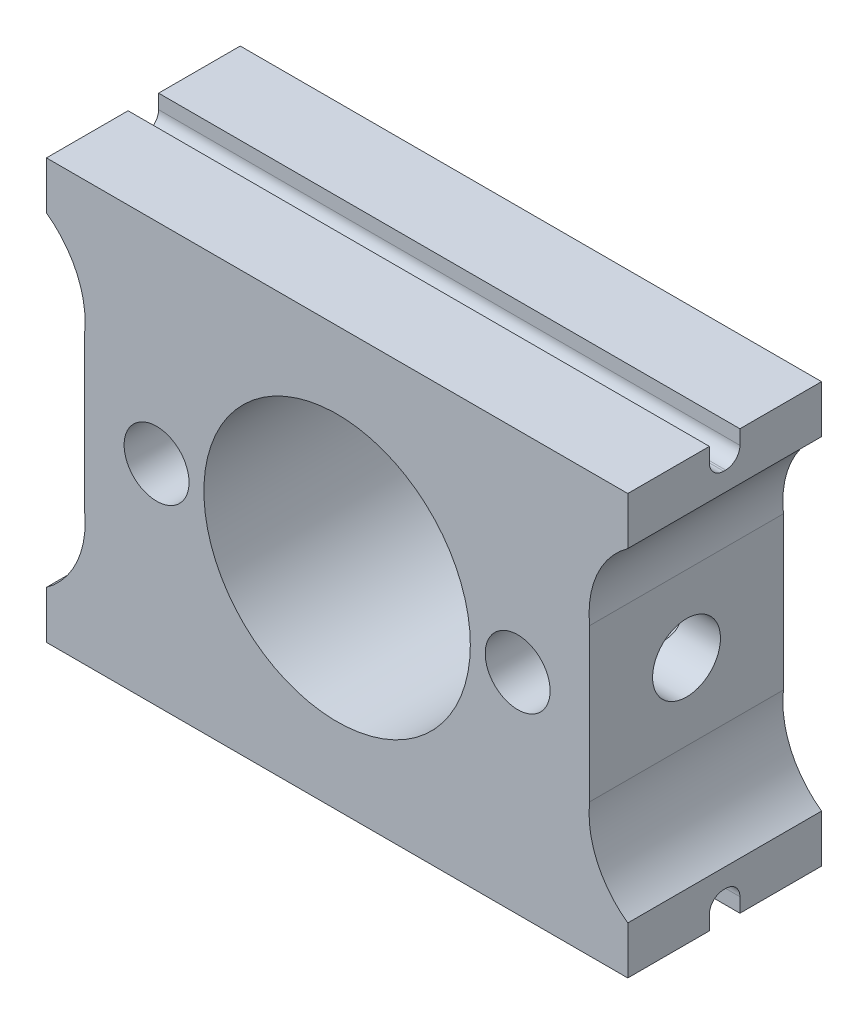
SolidWorks part; units mm, degrees
ref_plane "Front Plane" through (0, 0, 0) normal (0, 0, 1) x (1, 0, 0)
ref_plane "Top Plane" through (0, 0, 0) normal (0, 1, 0) x (1, 0, 0)
ref_plane "Right Plane" through (0, 0, 0) normal (1, 0, 0) x (0, 0, -1)
sketch "Sketch1" plane through (0, 0, 0) normal (0, 0, 1) x (1, 0, 0)
  line L0 (1, 7.5) -> (1, 3.5)
  line L1 (0, 0) -> (15.24, 0)
  line L2 (0, 0) -> (0, 11)
  line L3 (0, 11) -> (15.24, 11)
  line L4 (15.24, 0) -> (15.24, 11)
  line L5 (1, 7.5) -> (1, 11) construction
  line L6 (1, 3.5) -> (1, 0) construction
  line L7 (0, 5.5) -> (15.24, 5.5) construction
  line L8 (7.62, 11) -> (7.62, 0) construction
  line L9 (14.24, 7.5) -> (14.24, 3.5)
  arc A0 (0, 9.75) -> (1, 7.5) centre (-1.4231, 7.7703) cw
  arc A1 (0, 1.25) -> (1, 3.5) centre (-1.4231, 3.2297) ccw
  arc A2 (15.24, 1.25) -> (14.24, 3.5) centre (16.6631, 3.2297) cw
  arc A3 (15.24, 9.75) -> (14.24, 7.5) centre (16.6631, 7.7703) ccw
  circle A4 centre (7.62, 5.5) radius 3.4925
  circle A5 centre (2.8868, 5.5) radius 0.8509
  circle A6 centre (12.3532, 5.5) radius 0.8509
  dimension "D6" = 6.985
  dimension "D1" = 15.24
  dimension "D2" = 11
  dimension "D3" = 4
  dimension "D4" = 1.25
  dimension "D5" = 1
  dimension "D8" = 9.4664
extrude "Boss-Extrude1" add sketch "Sketch1" along normal blind 5.08 contours A3 L4 L3 L2 A0 L0 A1 L1 A2 L9 A4 A5 A6
sketch "Sketch2" plane through (14.24, 0, 0) normal (1, 0, 0) x (0, 0, -1)
  circle A0 centre (-2.54, 5.5) radius 0.89
  dimension "D1" = 1.78
extrude "Cut-Extrude1" cut sketch "Sketch2" against normal blind 2.286
sketch "Sketch3" plane through (1, 0, 0) normal (-1, 0, 0) x (0, 0, 1)
  circle A0 centre (2.54, 5.5) radius 0.89
  dimension "D1" = 1.78
extrude "Cut-Extrude2" cut sketch "Sketch3" against normal blind 2.286
ref_plane "Plane1" through (0, 5.5, 0) normal (0, -1, 0) x (-1, 0, 0)
sketch "Sketch4" plane through (15.24, 0, 0) normal (1, 0, 0) x (0, 0, -1)
  line L0 (-5.08, 0) -> (0, 0) construction
  line L2 (-2.94, 0) -> (-2.14, 0)
  line L3 (-2.94, 0) -> (-2.94, 0.376)
  line L4 (-2.566, 0.75) -> (-2.514, 0.75)
  line L5 (-2.14, 0) -> (-2.14, 0.376)
  line L6 (-2.94, 0.75) -> (-5.08, 0) construction
  line L7 (-2.14, 0.75) -> (0, 0) construction
  arc A0 (-2.14, 0.376) -> (-2.514, 0.75) centre (-2.514, 0.376) ccw
  arc A1 (-2.94, 0.376) -> (-2.566, 0.75) centre (-2.566, 0.376) cw
  dimension "D2" = 0.374
  dimension "D1" = 0.8
  dimension "D3" = 0.75
extrude "Cut-Extrude3" cut sketch "Sketch4" against normal through all
mirror "Mirror1" about plane through (0, 5.5, 0) normal (0, -1, 0) of "Cut-Extrude3"
